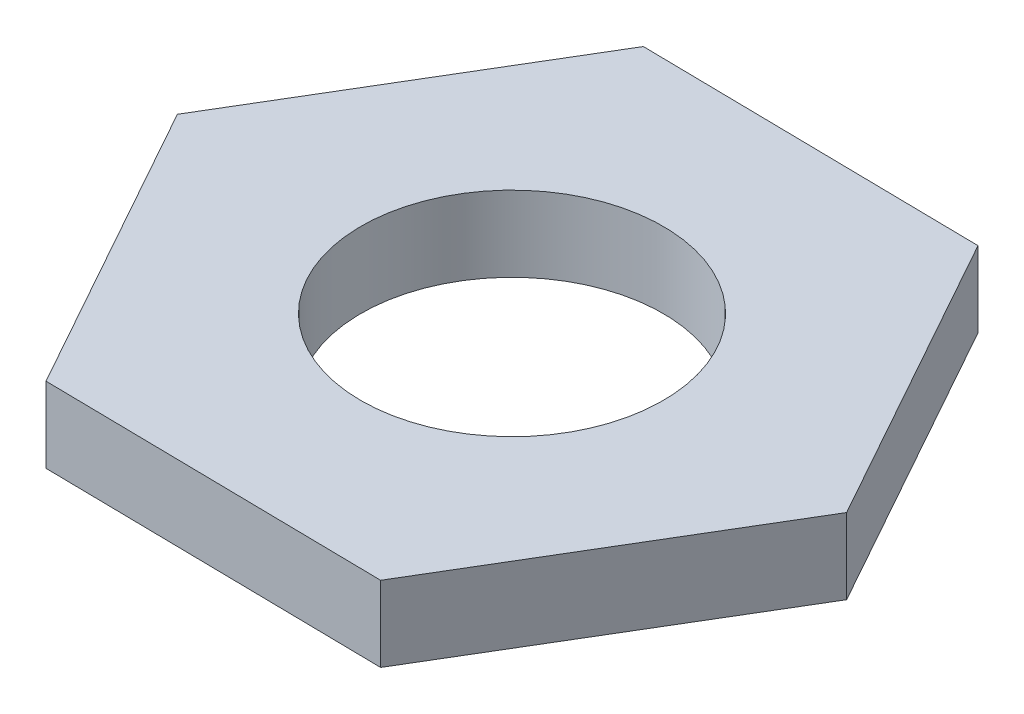
SolidWorks part; units mm, degrees
ref_plane "Alzado" through (0, 0, 0) normal (0, 0, 1) x (1, 0, 0)
ref_plane "Planta" through (0, 0, 0) normal (0, 1, 0) x (1, 0, 0)
ref_plane "Vista lateral" through (0, 0, 0) normal (1, 0, 0) x (0, 0, -1)
sketch "Croquis1" plane through (0, 0, 0) normal (0, 1, 0) x (1, 0, 0)
  line L1 (4.4995, -0.068) -> (2.3086, 3.8627)
  line L2 (2.3086, 3.8627) -> (-2.1909, 3.9307)
  line L3 (-2.1909, 3.9307) -> (-4.4995, 0.068)
  line L4 (-4.4995, 0.068) -> (-2.3086, -3.8627)
  line L5 (-2.3086, -3.8627) -> (2.1909, -3.9307)
  line L6 (2.1909, -3.9307) -> (4.4995, -0.068)
  circle A0 centre (0, 0) radius 2
  circle A1 centre (0, 0) radius 3.8971 construction
  point P3 (2.1909, 3.9307)
  dimension "D1" = 4
  dimension "D2" = 4.5
extrude "Saliente-Extruir1" add sketch "Croquis1" along normal blind 1
